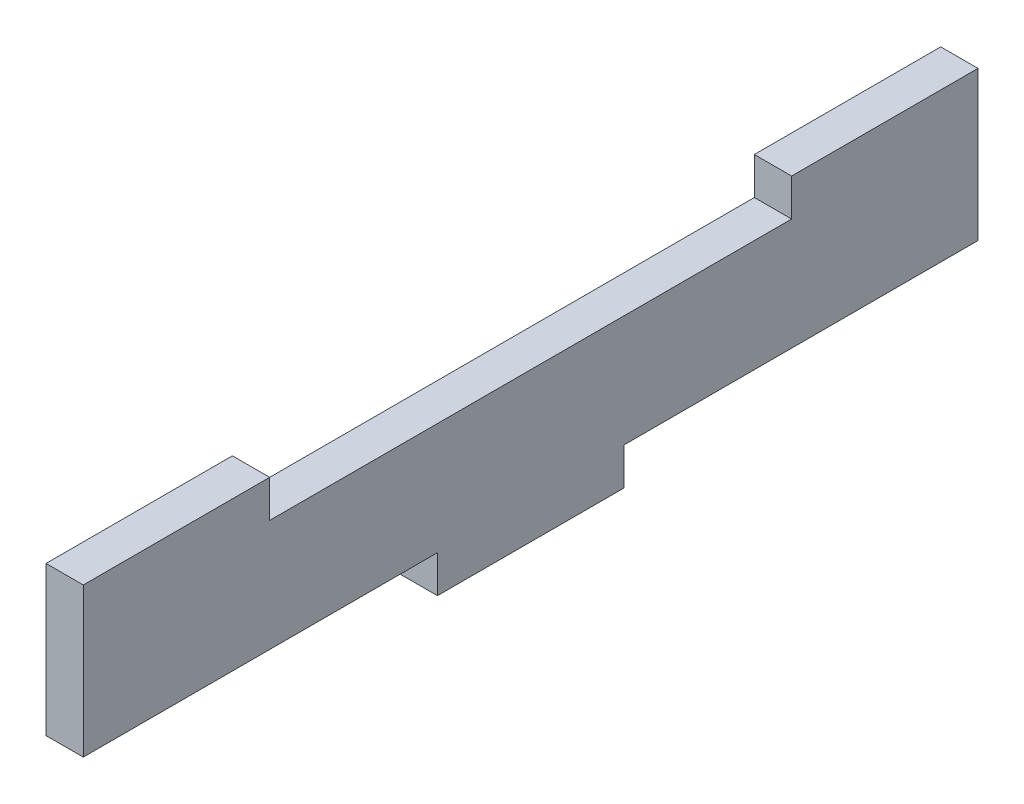
SolidWorks part; units mm, degrees
ref_plane "前视基准面" through (0, 0, 0) normal (0, 0, 1) x (1, 0, 0)
ref_plane "上视基准面" through (0, 0, 0) normal (0, 1, 0) x (1, 0, 0)
ref_plane "右视基准面" through (0, 0, 0) normal (1, 0, 0) x (0, 0, -1)
sketch "草图1" plane through (0, 0, 0) normal (1, 0, 0) x (0, 0, -1)
  line L0 (-47.5, 0) -> (0, 0)
  line L1 (-95, 15) -> (-25, 15)
  line L2 (-120, 15) -> (-120, 0)
  line L3 (-120, 0) -> (-72.5, 0)
  line L4 (0, 15) -> (0, 0)
  line L6 (-120, 15) -> (-120, 20)
  line L7 (-120, 20) -> (-95, 20)
  line L8 (-95, 15) -> (-95, 20)
  line L10 (0, 15) -> (0, 20)
  line L11 (0, 20) -> (-25, 20)
  line L12 (-25, 15) -> (-25, 20)
  line L14 (-72.5, 0) -> (-72.5, -5)
  line L15 (-72.5, -5) -> (-47.5, -5)
  line L16 (-47.5, 0) -> (-47.5, -5)
  dimension "D1" = 120
  dimension "D2" = 15
  dimension "D3" = 5
  dimension "D4" = 5
  dimension "D5" = 5
  dimension "D6" = 25
  dimension "D7" = 47.5
  dimension "D8" = 5
extrude "凸台-拉伸1" add sketch "草图1" along normal blind 5
